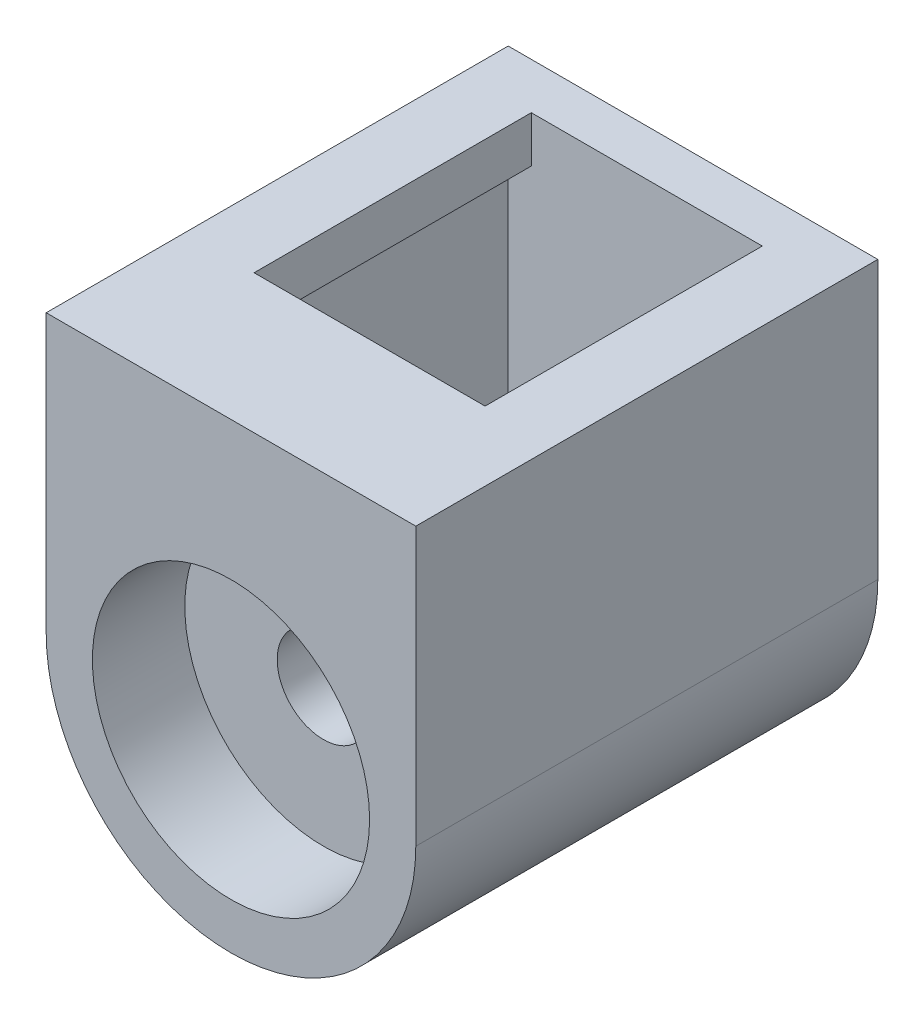
SolidWorks part; units mm, degrees
ref_plane "Front Plane" through (0, 0, 0) normal (0, 0, 1) x (1, 0, 0)
ref_plane "Top Plane" through (0, 0, 0) normal (0, 1, 0) x (1, 0, 0)
ref_plane "Right Plane" through (0, 0, 0) normal (1, 0, 0) x (0, 0, -1)
sketch "Sketch1" plane through (0, 0, 0) normal (0, 0, 1) x (1, 0, 0)
  circle A0 centre (0, 0) radius 7.5
  dimension "D1" = 15
extrude "Boss-Extrude1" add sketch "Sketch1" along normal blind 10
sketch "Sketch2" plane through (0, 0, 10) normal (0, 0, 1) x (1, 0, 0)
  line L0 (20, 0) -> (20, 30)
  line L1 (-20, 0) -> (-20, 30)
  line L2 (-20, 30) -> (20, 30)
  arc A0 (-20, 0) -> (20, 0) centre (0, 0) ccw
  dimension "D1" = 40
  dimension "D2" = 30
extrude "Boss-Extrude2" add sketch "Sketch2" along normal blind 50
sketch "Sketch3" plane through (0, 0, 60) normal (0, 0, 1) x (1, 0, 0)
  circle A0 centre (0, 0) radius 15
  dimension "D1" = 30
extrude "Cut-Extrude1" cut sketch "Sketch3" against normal blind 10
ref_plane "Plane1" through (0, 0, 15) normal (0, 0, -1) x (-1, 0, 0)
sketch "Sketch5" plane through (0, 0, 15) normal (0, 0, -1) x (-1, 0, 0)
  line L0 (15, 25) -> (-15, 25)
  line L1 (-15, 25) -> (-15, 0)
  line L2 (15, 0) -> (15, 25)
  line L3 (20, 0) -> (20, 30)
  line L4 (20, 30) -> (-20, 30)
  line L5 (-20, 30) -> (-20, 0)
  line L6 (20, 0) -> (20, 30)
  line L7 (20, 30) -> (-20, 30)
  line L8 (-20, 30) -> (-20, 0)
  arc A0 (-15, 0) -> (15, 0) centre (0, 0) ccw
  arc A1 (-20, 0) -> (20, 0) centre (0, 0) ccw
  arc A2 (-20, 0) -> (20, 0) centre (0, 0) ccw
  dimension "D1" = 0
  dimension "D2" = 5
extrude "Cut-Extrude2" cut sketch "Sketch5" against normal blind 30 contours L0 L1 A0 L2
sketch "Sketch6" plane through (0, 30, 0) normal (0, 1, 0) x (1, 0, 0)
  line L0 (0, -15) -> (0, -39.2457) construction
  line L1 (22, -15) -> (-22, -15) construction
  line L3 (12.5, -45) -> (-12.5, -45)
  line L4 (12.5, -45) -> (12.5, -15)
  line L5 (12.5, -15) -> (-12.5, -15)
  line L6 (-12.5, -45) -> (-12.5, -15)
  line L7 (12.5, -45) -> (-12.5, -15) construction
  line L8 (12.5, -15) -> (-12.5, -45) construction
  point P5 (0, -30)
  dimension "D1" = 30
  dimension "D2" = 25
extrude "Cut-Extrude3" cut sketch "Sketch6" against normal blind 30
sketch "Sketch7" plane through (0, 0, 50) normal (0, 0, 1) x (1, 0, 0)
  circle A0 centre (0, 0) radius 5
  dimension "D1" = 10
extrude "Cut-Extrude4" cut sketch "Sketch7" against normal blind 30
sketch "Sketch8" plane through (0, 0, 0) normal (0, 0, -1) x (-1, 0, 0)
  circle A0 centre (0, 0) radius 5.1
  dimension "D1" = 10.2
extrude "Cut-Extrude5" cut sketch "Sketch8" against normal blind 5
sketch "Sketch9" plane through (0, 0, 0) normal (0, 1, 0) x (1, 0, 0)
  line L0 (5.1, 0) -> (-5.1, 0) construction
  circle A0 centre (0, -2.5) radius 1.5
  dimension "D1" = 3
  dimension "D2" = 2.5
extrude "Cut-Extrude6" cut sketch "Sketch9" against normal through all both and the other way through all
pattern_circular "CirPattern1" count 2 every 90 about axis through (0, 0, 0) along (0, 0, 1) of "Cut-Extrude6"
